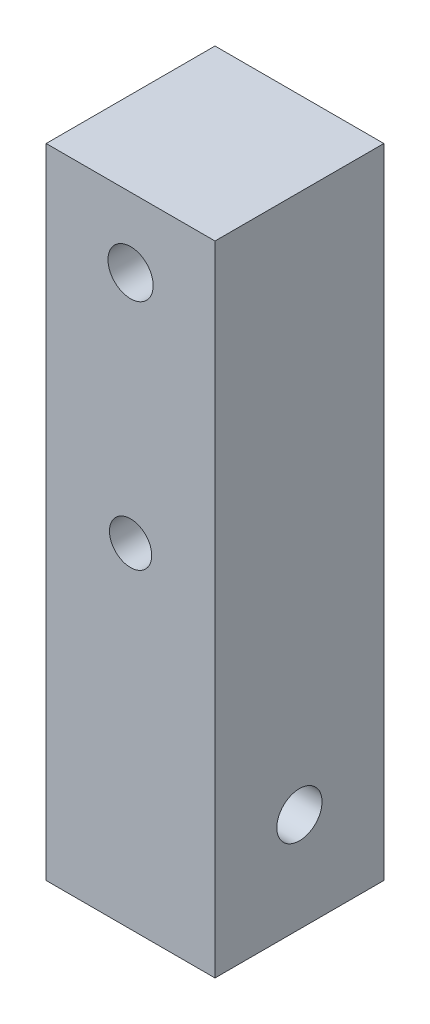
SolidWorks part; units mm, degrees
ref_plane "Front Plane" through (0, 0, 0) normal (0, 0, 1) x (1, 0, 0)
ref_plane "Top Plane" through (0, 0, 0) normal (0, 1, 0) x (1, 0, 0)
ref_plane "Right Plane" through (0, 0, 0) normal (1, 0, 0) x (0, 0, -1)
sketch "Sketch1" plane through (0, 0, 0) normal (0, 1, 0) x (1, 0, 0)
  line L1 (-6.35, -6.35) -> (6.35, -6.35)
  line L2 (-6.35, -6.35) -> (-6.35, 6.35)
  line L3 (-6.35, 6.35) -> (6.35, 6.35)
  line L4 (6.35, -6.35) -> (6.35, 6.35)
  line L5 (-6.35, -6.35) -> (6.35, 6.35) construction
  line L6 (-6.35, 6.35) -> (6.35, -6.35) construction
  point P0 (0, 0)
  dimension "D1" = 12.7
  dimension "D2" = 12.7
extrude "Boss-Extrude1" add sketch "Sketch1" along normal blind 48.006
sketch "Sketch2" plane through (0, 0, 6.35) normal (0, 0, 1) x (1, 0, 0)
  line L0 (-6.35, 0) -> (6.35, 0) construction
  line L1 (6.35, 48.006) -> (6.35, 0) construction
  circle A0 centre (0, 25.146) radius 1.5875
  dimension "D2" = 3.175
  dimension "D1" = 25.146
  dimension "D3" = 6.35
extrude "Cut-Extrude1" cut sketch "Sketch2" against normal through all
sketch "Sketch3" plane through (0, 0, 6.35) normal (0, 0, 1) x (1, 0, 0)
  circle A0 centre (0, 42.7672) radius 1.7
extrude "Cut-Extrude2" cut sketch "Sketch3" against normal through all
sketch "Sketch4" plane through (6.35, 0, 0) normal (1, 0, 0) x (0, 0, -1)
  circle A0 centre (0, 7.4612) radius 1.7
extrude "Cut-Extrude3" cut sketch "Sketch4" against normal through all
